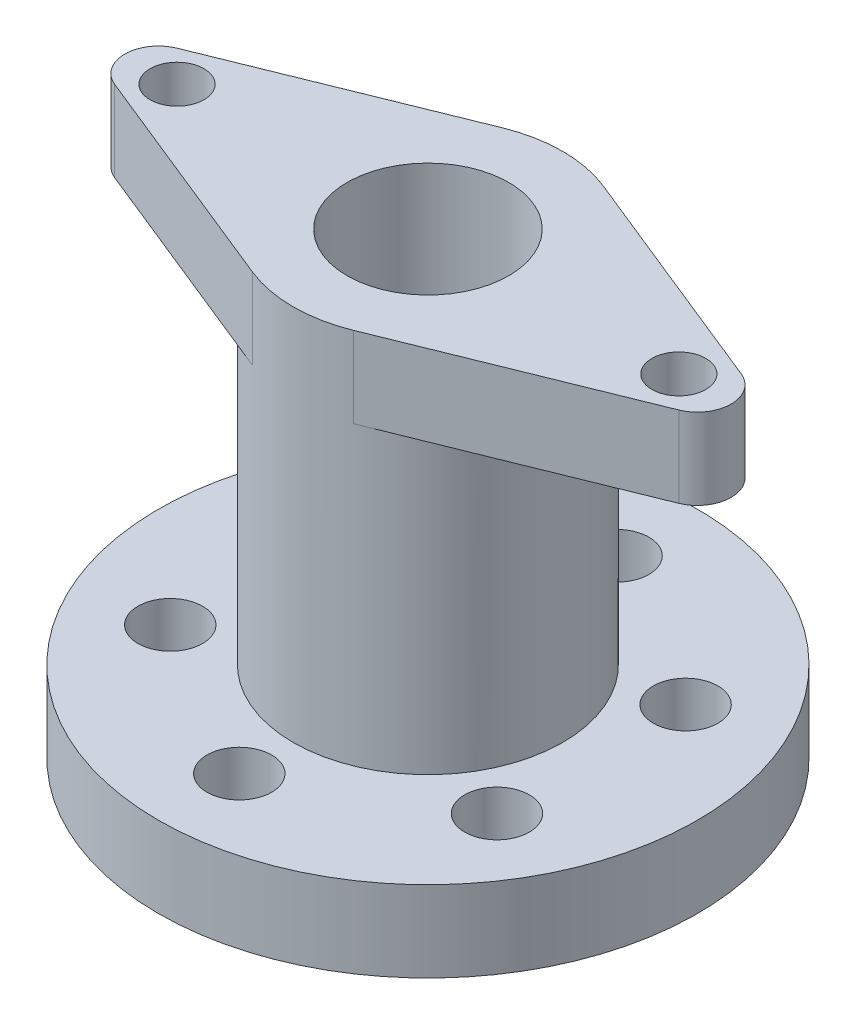
SolidWorks part; units mm, degrees
ref_plane "Front Plane" through (0, 0, 0) normal (0, 0, 1) x (1, 0, 0)
ref_plane "Top Plane" through (0, 0, 0) normal (0, 1, 0) x (1, 0, 0)
ref_plane "Right Plane" through (0, 0, 0) normal (1, 0, 0) x (0, 0, -1)
sketch "Sketch1" plane through (0, 0, 0) normal (0, 1, 0) x (1, 0, 0)
  circle A0 centre (0, 0) radius 500
  circle A1 centre (0, 0) radius 350
  circle A2 centre (0, 350) radius 60
  circle A3 centre (303.1089, 175) radius 60
  circle A4 centre (303.1089, -175) radius 60
  circle A5 centre (0, -350) radius 60
  circle A6 centre (-303.1089, -175) radius 60
  circle A7 centre (-303.1089, 175) radius 60
  point P18 (0, 0)
  dimension "D1" = 1000
  dimension "D2" = 700
  dimension "D3" = 120
  dimension "D4" = 6
extrude "Boss-Extrude1" add sketch "Sketch1" along normal blind 150 contours A0 A7 A1 A2 A3 A4 A5 A6 | A7 A1 A6 A5 A4 A3 A2
sketch "Sketch3" plane through (0, 0, 0) normal (0, 1, 0) x (1, 0, 0)
  circle A0 centre (0, 0) radius 250
  circle A1 centre (0, 0) radius 150
  dimension "D1" = 500
  dimension "D2" = 300
extrude "Boss-Extrude2" add sketch "Sketch3" along normal blind 700
sketch "Sketch5" plane through (0, 700, 0) normal (0, 1, 0) x (1, 0, 0)
  line L0 (0, 0) -> (574.5092, 0) construction
  line L1 (465.5598, 0) -> (-465.5598, 0) construction
  line L2 (-523.4375, 57.9391) -> (-93.75, 231.7562)
  line L3 (-523.4375, -57.9391) -> (-93.75, -231.7562)
  line L4 (0, 0) -> (0, -330.5282) construction
  line L5 (0, -330.5282) -> (0, 318.4422) construction
  line L6 (523.4375, -57.9391) -> (93.75, -231.7562)
  line L7 (523.4375, 57.9391) -> (93.75, 231.7562)
  arc A0 (-523.4375, 57.9391) -> (-523.4375, -57.9391) centre (-500, 0) ccw
  circle A2 centre (0, 0) radius 250 construction
  circle A3 centre (0, 0) radius 250 construction
  arc A4 (523.4375, 57.9391) -> (523.4375, -57.9391) centre (500, 0) cw
  circle A5 centre (-465.5598, 0) radius 50
  circle A6 centre (465.5598, 0) radius 50
  circle M4 centre (0, 0) radius 250
  circle M5 centre (0, 0) radius 150
  dimension "D1" = 125
  dimension "D3" = 100
  dimension "D4" = 100
  dimension "D2" = 500
extrude "Boss-Extrude3" add sketch "Sketch5" along normal blind 150 contours L2 A0 L3 A5 M4 | A4 L7 L6 A6 M4 | M4 M5
